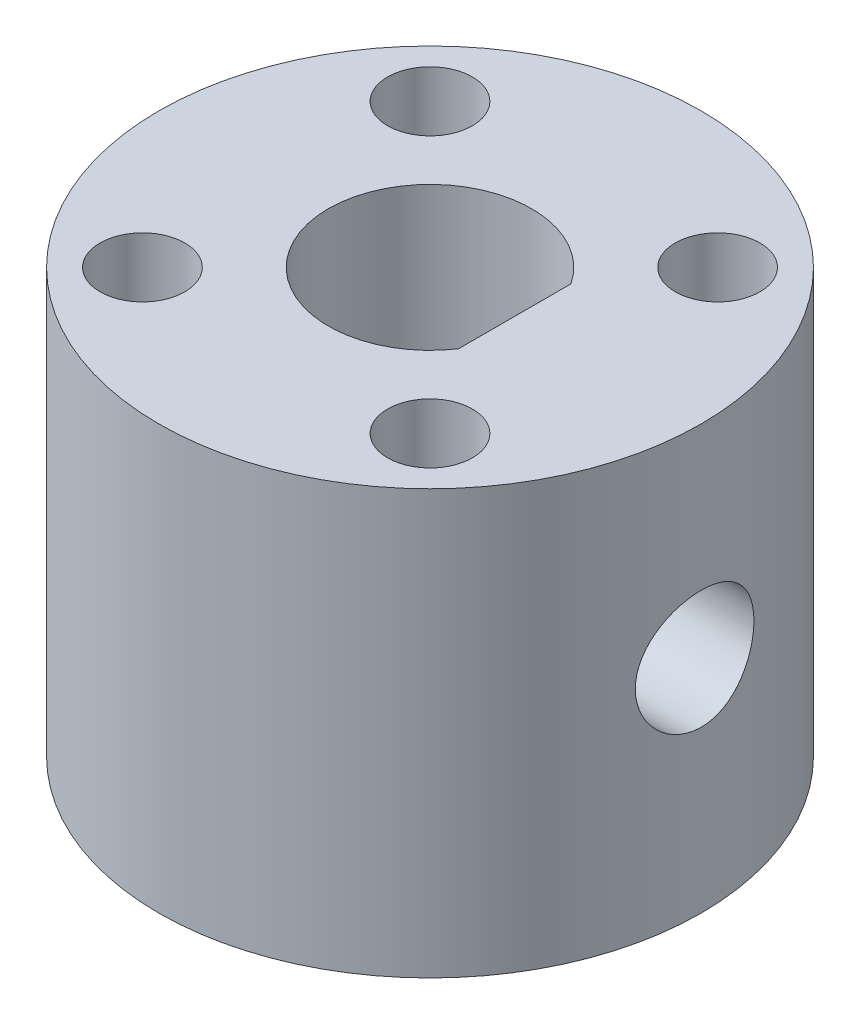
SolidWorks part; units mm, degrees
ref_plane "前视基准面" through (0, 0, 0) normal (0, 0, 1) x (1, 0, 0)
ref_plane "上视基准面" through (0, 0, 0) normal (0, 1, 0) x (1, 0, 0)
ref_plane "右视基准面" through (0, 0, 0) normal (1, 0, 0) x (0, 0, -1)
sketch "草图1" plane through (0, 0, 0) normal (0, 1, 0) x (1, 0, 0)
  line L0 (2.5, 1.6583) -> (2.5, -1.6583)
  line L1 (2.55, 1.6733) -> (2.55, -1.6733) construction
  line L2 (0, 0) -> (4.2426, 4.2426) construction
  arc A0 (2.5, 1.6583) -> (2.5, -1.6583) centre (0, 0) ccw
  circle A1 centre (0, 0) radius 6 construction
  circle A2 centre (4.2426, 4.2426) radius 1.25
  circle A3 centre (4.2426, -4.2426) radius 1.25
  circle A4 centre (-4.2426, -4.2426) radius 1.25
  circle A5 centre (-4.2426, 4.2426) radius 1.25
  circle A6 centre (0, 0) radius 8
  arc A7 (2.55, 1.6733) -> (2.55, -1.6733) centre (0, 0) ccw construction
  point P15 (0, 0)
  point P20 (0, 0)
  dimension "D1" = 6
  dimension "D2" = 12
  dimension "D3" = 2.5
  dimension "D5" = 16
  dimension "D6" = 2.5
  dimension "D7" = 0.05
  dimension "D4" = 4
extrude "凸台-拉伸1" add sketch "草图1" along normal blind 12.5
cosmetic thread "装饰螺纹线2" parameters "D2"=3
cosmetic thread "装饰螺纹线3" parameters "D2"=3
cosmetic thread "装饰螺纹线4" parameters "D2"=3
cosmetic thread "装饰螺纹线5" parameters "D2"=3
sketch "草图3" plane through (2.5, 0, 0) normal (-1, 0, 0) x (0, 0, 1)
  line L0 (5.4926, 12.5) -> (2.9926, 12.5) construction
  circle A0 centre (0, 6.5) radius 1.75
  dimension "D1" = 3.5
  dimension "D2" = 6
extrude "切除-拉伸1" cut sketch "草图3" against normal blind 10
cosmetic thread "装饰螺纹线1" parameters "D2"=5
